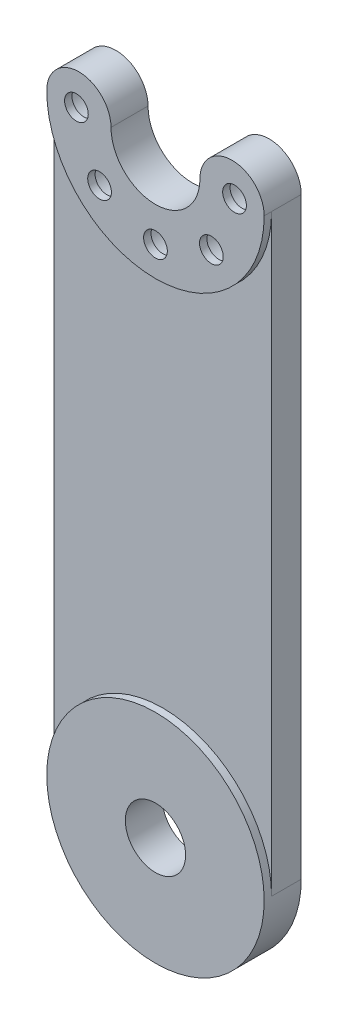
SolidWorks part; units mm, degrees
ref_plane "Plano frontal" through (0, 0, 0) normal (0, 0, 1) x (1, 0, 0)
ref_plane "Plano superior" through (0, 0, 0) normal (0, 1, 0) x (1, 0, 0)
ref_plane "Plano direito" through (0, 0, 0) normal (1, 0, 0) x (0, 0, -1)
sketch "Esboço1" plane through (0, 0, 0) normal (0, 0, 1) x (1, 0, 0)
  arc A2 (-4.5, 0) -> (4.5, 0) centre (0, 0) ccw
  arc A3 (11, 0) -> (-11, 0) centre (0, 0) cw
  arc A4 (-4, 0) -> (4, 0) centre (0, 0) ccw construction
  arc A5 (11, 0) -> (4.5, 0) centre (7.75, 0) ccw
  arc A6 (-4.5, 0) -> (-11, 0) centre (-7.75, 0) ccw
  arc A9 (-11, 0) -> (11, 0) centre (0, 0) ccw construction
  dimension "D1" = 0.5
extrude "Ressalto-extrusão1" add sketch "Esboço1" against normal offset from surface (0.75 mm away) 2
sketch "Esboço3" plane through (0, 0, -0.75) normal (0, 0, -1) x (-1, 0, 0)
  line L0 (-11, 0) -> (-11, -60)
  line L2 (11, -60) -> (11, 0)
  arc A0 (11, 0) -> (4.5, 0) centre (7.75, 0) ccw construction
  arc A1 (-4.5, 0) -> (4.5, 0) centre (0, 0) ccw construction
  arc A2 (-4.5, 0) -> (-11, 0) centre (-7.75, 0) ccw construction
  arc A3 (11, 0) -> (4.5, 0) centre (7.75, 0) ccw
  arc A4 (-4.5, 0) -> (4.5, 0) centre (0, 0) ccw
  arc A5 (-4.5, 0) -> (-11, 0) centre (-7.75, 0) ccw
  arc A9 (-11, -60) -> (11, -60) centre (0, -60) ccw
extrude "Ressalto-extrusão2" add sketch "Esboço3" along normal blind 3
hole_wizard "Rebaixo para SHCS M21" positions "Sketch1" profile "Sketch2" counterbore size "M2" standard "Ansi Metric" end condition up to next
sketch "Sketch1" plane through (0, 0, -3.75) normal (0, 0, -1) x (-1, 0, 0)
  line L0 (0, 0) -> (-8, 0) construction
  line L1 (0, 0) -> (-5.6569, -5.6569) construction
  line L2 (0, 0) -> (0, -8) construction
  line L3 (0, 0) -> (5.6569, -5.6569) construction
  line L4 (0, 0) -> (8, 0) construction
  arc A0 (-9, 0) -> (-7, 0) centre (-8, 0) ccw construction
  point P0 (-8, 0)
  point P16 (-5.6569, -5.6569)
  point P18 (0, -8)
  point P20 (5.6569, -5.6569)
  point P22 (8, 0)
  dimension "D1" = 5
sketch "Sketch2" plane through (8, 0, -3.75) normal (1, 0, 0) x (0, 1, 0)
  line L0 (0, 0) -> (0, 3.75)
  line L1 (0, 3.75) -> (1.2, 3.75)
  line L3 (1.2, 3.75) -> (1.2, 3)
  line L4 (1.2, 3) -> (2.2, 3)
  line L5 (2.2, 3) -> (2.2, 0)
  line L7 (2.2, 0) -> (0, 0)
  line L11 (0, -6.35) -> (0, 107.95) construction
  dimension "Thru Hole Dia." = 2.4
  dimension "Thru Hole Depth" = 3.75
  dimension "C'Bore Dia." = 4.4
  dimension "C'Bore Depth" = 3
sketch "Esboço4" plane through (0, 0, -0.75) normal (0, 0, 1) x (1, 0, 0)
  circle A0 centre (0, -60) radius 11
  arc A1 (-11, -60) -> (11, -60) centre (0, -60) ccw construction
extrude "Ressalto-extrusão3" add sketch "Esboço4" along normal up to surface (0.75 mm away)
sketch "Esboço5" plane through (0, 0, -3.75) normal (0, 0, -1) x (-1, 0, 0)
  circle A0 centre (0, -60) radius 3.05 construction
  circle A1 centre (0, -60) radius 3.05
extrude "Corte-extrusão1" cut sketch "Esboço5" against normal through all
